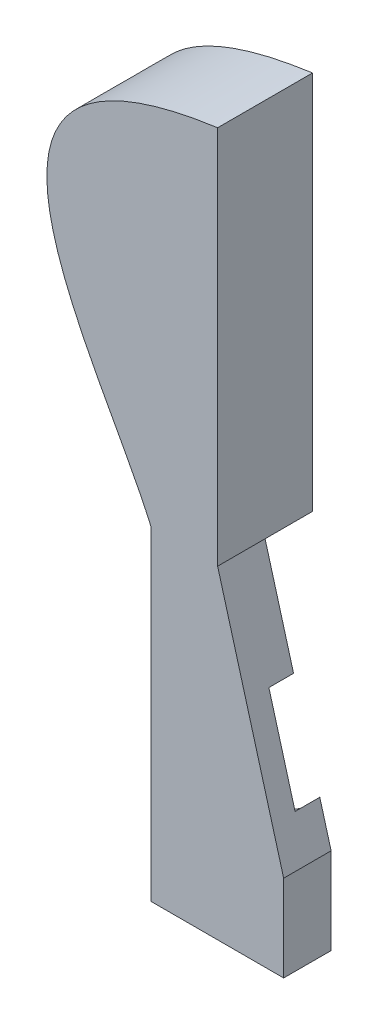
SolidWorks part; units mm, degrees
ref_plane "Front Plane" through (0, 0, 0) normal (0, 0, 1) x (1, 0, 0)
ref_plane "Top Plane" through (0, 0, 0) normal (0, 1, 0) x (1, 0, 0)
ref_plane "Right Plane" through (0, 0, 0) normal (1, 0, 0) x (0, 0, -1)
sketch "Sketch1" plane through (0, 0, 0) normal (0, 0, 1) x (1, 0, 0)
  line L0 (0.2218, 84.8283) -> (0.2207, 284.8283)
  line L1 (35, -85.625) -> (-35, -85.625)
  line L4 (-35, -85.625) -> (-35, 85.625)
  line L5 (35, -85.625) -> (-35, 85.625) construction
  line L6 (35, 85.625) -> (-35, -85.625) construction
  line L7 (0.2218, 84.8283) -> (35, -40.1019)
  line L8 (35, -40.1019) -> (35, -85.625)
  spline S0 degree 3 poles (0.2207, 284.8283) (-159.9787, 262.6066) (-63.0007, 150.139) (-35, 85.625) knots 0 0 0 0 1 1 1 1
  point P1 (0, 0)
  dimension "D1" = 70
  dimension "D2" = 200
extrude "Boss-Extrude1" add sketch "Sketch1" along normal blind 50
sketch "Sketch2" plane through (0, 0, 50) normal (0, 0, 1) x (1, 0, 0)
  circle A0 centre (0, 0) radius 20
sketch "Sketch3" plane through (22.122, 6.1583, 0) normal (0.9634, 0.2682, 0) x (0, 0, -1)
  line L0 (-50, 81.6614) -> (0, 81.6614) construction
  line L1 (-25, 81.6614) -> (-25, -107.2994)
  line L2 (-25, -107.2994) -> (41.3764, -107.2994)
  line L5 (41.3764, -107.2994) -> (41.3764, 81.6614)
  line L6 (41.3764, 81.6614) -> (-25, 81.6614)
extrude "Cut-Extrude1" cut sketch "Sketch3" against normal through all
sketch "Sketch4" plane through (0, 0, 25) normal (0, 0, -1) x (-1, 0, 0)
  circle A0 centre (0, 0) radius 34.5
extrude "Cut-Extrude2" cut sketch "Sketch4" against normal blind 13
